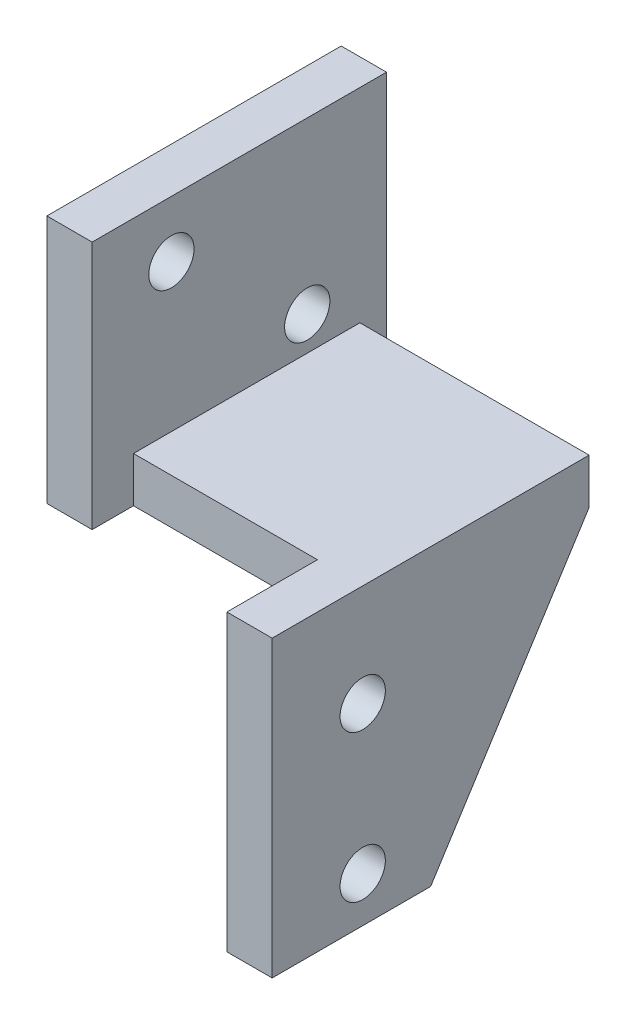
SolidWorks part; units mm, degrees
ref_plane "Plan de face" through (0, 0, 0) normal (0, 0, 1) x (1, 0, 0)
ref_plane "Plan de dessus" through (0, 0, 0) normal (0, 1, 0) x (1, 0, 0)
ref_plane "Plan de droite" through (0, 0, 0) normal (1, 0, 0) x (0, 0, -1)
sketch "Esquisse1" plane through (0, 0, 0) normal (0, 0, 1) x (1, 0, 0)
  line L1 (0, 0) -> (24.25, 0)
  line L2 (0, 0) -> (0, 16)
  line L3 (0, 16) -> (24.25, 16)
  line L4 (24.25, 0) -> (24.25, 16)
  line L5 (0, 0) -> (24.25, 0)
  line L6 (0, 0) -> (0, -24)
  line L7 (0, -24) -> (24.25, -24)
  line L8 (24.25, 0) -> (24.25, -24)
  line L9 (4, 16) -> (24.25, 16)
  line L10 (4, 16) -> (4, 2)
  line L11 (4, 2) -> (24.25, 2)
  line L12 (24.25, 16) -> (24.25, 2)
  line L13 (0, -24) -> (20.25, -24)
  line L14 (0, -24) -> (0, -2)
  line L15 (0, -2) -> (20.25, -2)
  line L16 (20.25, -24) -> (20.25, -2)
  dimension "D1" = 24.25
  dimension "D2" = 16
  dimension "D3" = 24
  dimension "D4" = 22
  dimension "D5" = 14
  dimension "D6" = 4
  dimension "D7" = 4
extrude "Boss.-Extru.1" add sketch "Esquisse1" along normal blind 20 contours L11 L10 L3 L2 L1 L4 | L16 L7 L8 L1 L6 L15
sketch "Esquisse3" plane through (0, 0, 0) normal (0, 0, -1) x (-1, 0, 0)
  line L1 (-4, 16) -> (0, 16)
  line L2 (-4, 16) -> (-4, -2)
  line L3 (-4, -2) -> (0, -2)
  line L4 (0, 16) -> (0, -2)
extrude "Boss.-Extru.2" add sketch "Esquisse3" along normal blind 20
sketch "Esquisse4" plane through (0, 0, 20) normal (0, 0, 1) x (1, 0, 0)
  line L1 (0, 16) -> (4, 16)
  line L2 (0, 16) -> (0, -2)
  line L3 (0, -2) -> (4, -2)
  line L4 (4, 16) -> (4, -2)
extrude "Boss.-Extru.3" add sketch "Esquisse4" along normal blind 20
sketch "Esquisse5" plane through (0, 0, 0) normal (-1, 0, 0) x (0, 0, 1)
  line L0 (40, 16) -> (-20, 16) construction
  line L1 (0, -2) -> (20, -2)
  line L2 (0, -2) -> (0, 16)
  line L3 (0, 16) -> (20, 16)
  line L4 (20, -2) -> (20, 16)
  line L5 (40, -2) -> (-20, -2) construction
  line L6 (20, 16) -> (23.65, 16)
  line L7 (20, 16) -> (20, -2)
  line L8 (20, -2) -> (23.65, -2)
  line L9 (23.65, 16) -> (23.65, -2)
  line L11 (23.65, 16) -> (40, 16)
  line L12 (23.65, 16) -> (23.65, -2)
  line L13 (23.65, -2) -> (40, -2)
  line L14 (40, 16) -> (40, -2)
  line L15 (0, 16) -> (-2.35, 16)
  line L16 (0, 16) -> (0, -2)
  line L17 (0, -2) -> (-2.35, -2)
  line L18 (-2.35, 16) -> (-2.35, -2)
  line L19 (-2.35, 16) -> (-20, 16)
  line L20 (-2.35, 16) -> (-2.35, -2)
  line L21 (-2.35, -2) -> (-20, -2)
  line L22 (-20, 16) -> (-20, -2)
  circle A0 centre (4.65, 5) radius 2
  circle A1 centre (16.65, 15) radius 2
  point P22 (0, 0)
  line M8 (40, 16) -> (-20, 16)
  line M9 (-20, 16) -> (-20, -2)
  line M10 (-20, -2) -> (40, -2)
  line M11 (40, -2) -> (40, 16)
  dimension "D4" = 4
  dimension "D5" = 4
  dimension "D1" = 20
  dimension "D2" = 7
  dimension "D3" = 10
  dimension "D6" = 4.65
  dimension "D7" = 12
  dimension "D8" = 2.35
  dimension "D9" = 7
extrude "Enlèv. mat.-Extru.1" cut sketch "Esquisse5" against normal blind 20 contours L18 M8 M9 M10 | L9 M8 M10 M11 | A1 | A0
sketch "Esquisse6" plane through (0, 16, 0) normal (0, 1, 0) x (1, 0, 0)
  line L1 (0, 2.35) -> (4, 2.35)
  line L2 (0, 2.35) -> (0, -23.65)
  line L3 (0, -23.65) -> (4, -23.65)
  line L4 (4, 2.35) -> (4, -23.65)
extrude "Boss.-Extru.4" add sketch "Esquisse6" along normal blind 4
sketch "Esquisse7" plane through (0, 0, 0) normal (-1, 0, 0) x (0, 0, 1)
  circle A0 centre (16.65, 15) radius 2
extrude "Enlèv. mat.-Extru.2" cut sketch "Esquisse7" against normal blind 4
sketch "Esquisse8" plane through (20.25, 0, 0) normal (-1, 0, 0) x (0, 0, 1)
  line L0 (23.65, -2) -> (-2.35, -2) construction
  line L2 (20, -24) -> (20, -2) construction
  circle A0 centre (20, -7) radius 2
  circle A1 centre (20, -20) radius 2
  dimension "D1" = 4
  dimension "D2" = 4
  dimension "D3" = 5
  dimension "D4" = 13
  dimension "D5" = 0
  dimension "D6" = 0
extrude "Enlèv. mat.-Extru.3" cut sketch "Esquisse8" against normal blind 4 contours A0 | A1
sketch "Esquisse9" plane through (0, 0, 20) normal (0, 0, 1) x (1, 0, 0)
  line L1 (20.25, -24) -> (24.25, -24)
  line L2 (20.25, -24) -> (20.25, 2)
  line L3 (20.25, 2) -> (24.25, 2)
  line L4 (24.25, -24) -> (24.25, 2)
extrude "Boss.-Extru.5" add sketch "Esquisse9" along normal blind 8
sketch "Esquisse11" plane through (20.25, 0, 0) normal (-1, 0, 0) x (0, 0, 1)
  line L0 (20, -5) -> (20, -9) construction
  line L1 (0, -2) -> (28, -2)
  line L2 (0, -2) -> (0, -24)
  line L3 (0, -24) -> (28, -24)
  line L4 (28, -2) -> (28, -24)
  line L5 (20, -18) -> (20, -22) construction
  line L6 (14, -24) -> (0, -2)
  circle A0 centre (20, -7) radius 2
  circle A1 centre (20, -20) radius 2
  line M3 (0, -2) -> (0, -24)
  line M4 (0, -24) -> (28, -24)
  line M7 (20, -5) -> (20, -9)
  line M10 (20, -18) -> (20, -22)
extrude "Enlèv. mat.-Extru.5" cut sketch "Esquisse11" against normal blind 8 contours A0 M7 | A1 M10 | L6 M4 M3
